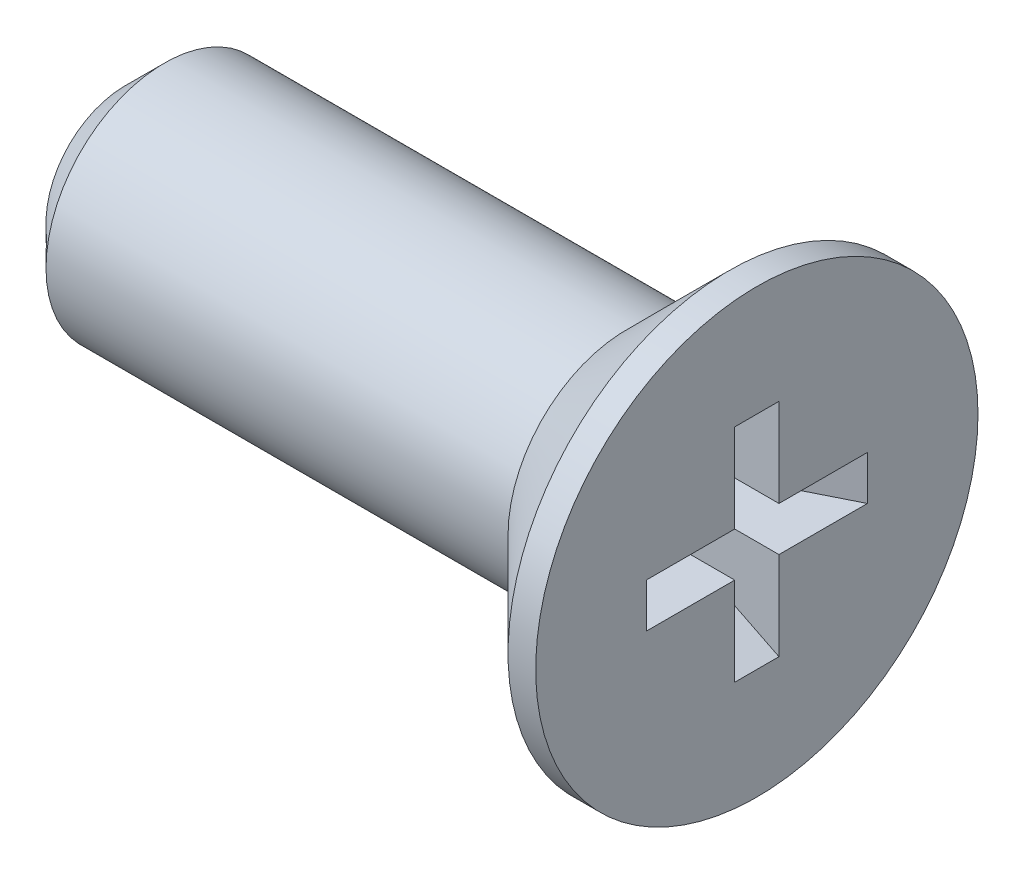
SolidWorks part; units mm, degrees
material "09Г2С"
ref_plane "Спереди" through (0, 0, 0) normal (0, 0, 1) x (1, 0, 0)
ref_plane "Сверху" through (0, 0, 0) normal (0, 1, 0) x (1, 0, 0)
ref_plane "Справа" through (0, 0, 0) normal (1, 0, 0) x (0, 0, -1)
sketch "Эскиз1" plane through (0, 0, 0) normal (1, 0, 0) x (0, 0, -1)
  circle A0 centre (0, 0) radius 1.5
  dimension "d1" = 3
extrude "Длина винта" add sketch "Эскиз1" against normal blind 8
cosmetic thread "Резьба d3" parameters "Длина резьбы b"=20, "Внутр диаметр резьбы d3"=2.387
chamfer "Фаска резьбы" distance 0.5 angle 45 1 edges at (-8, 0, -1.5)
sketch "Эскиз7" plane through (0, 0, 0) normal (0, 0, 1) x (1, 0, 0)
  line L0 (0, 0) -> (0, 2.8)
  line L1 (0, 2.8) -> (-0.35, 2.8)
  line L2 (-0.35, 2.8) -> (-1.65, 1.5)
  line L3 (0, 1.5) -> (-7.5, 1.5) construction
  line L4 (-1.65, 1.5) -> (-1.65, 0)
  line L5 (-1.65, 0) -> (0, 0)
  line L6 (0, 0) -> (-8, 0) construction
  line L7 (-8, 1.5) -> (-8, -1.5) construction
  line L8 (-0.35, -2.8) -> (-1.65, -1.5) construction
  dimension "Высота головки k" = 1.65
  dimension "Диаметр головки Dk" = 5.6
  dimension "D3" = 90
revolve "Головка " add sketch "Эскиз7" angle 360 about L6
sketch "Эскиз10" plane through (0, 0, 0) normal (0, 0, 1) x (1, 0, 0)
  line L1 (0, 1.4) -> (0, -1.4)
  line L2 (-1.6979, -0.28) -> (-1.6979, 0.28)
  line L3 (0, 0) -> (-1.6979, 0) construction
  line L5 (0, 1.4) -> (-1.5, 0.6521)
  line L6 (-1.5, 0.6521) -> (-1.6979, 0.28)
  line L7 (-1.6979, -0.28) -> (-1.5, -0.6521)
  line L8 (-1.5, -0.6521) -> (0, -1.4)
  dimension "m" = 2.8
  dimension "D1" = 28
  dimension "D2" = 26.5
  dimension "h" = 1.5
  dimension "D3" = 0.56
extrude "Вырез-Вытянуть1" cut sketch "Эскиз10" against normal mid plane 0.56
pattern_circular "Круговой массив1" count 2 over 90 about axis through (0, 0, 0) along (1, 0, 0) of "Вырез-Вытянуть1"
sketch "Эскиз11" plane through (0, 0, 0) normal (0, 0, 1) x (1, 0, 0)
  line L0 (-10.928, 1.5) -> (-1.65, 1.5)
  line L1 (-1.65, 1.5) -> (0, 3.15)
  line L2 (0, 3.15) -> (0, 0)
  line L3 (-10.928, 1.5) -> (-10.928, 0)
  line L4 (-10.928, 0) -> (0, 0)
  dimension "D1" = 3.15
equation "\"D1@Вырез-Вытянуть1\"=\"D3@Эскиз10\""
